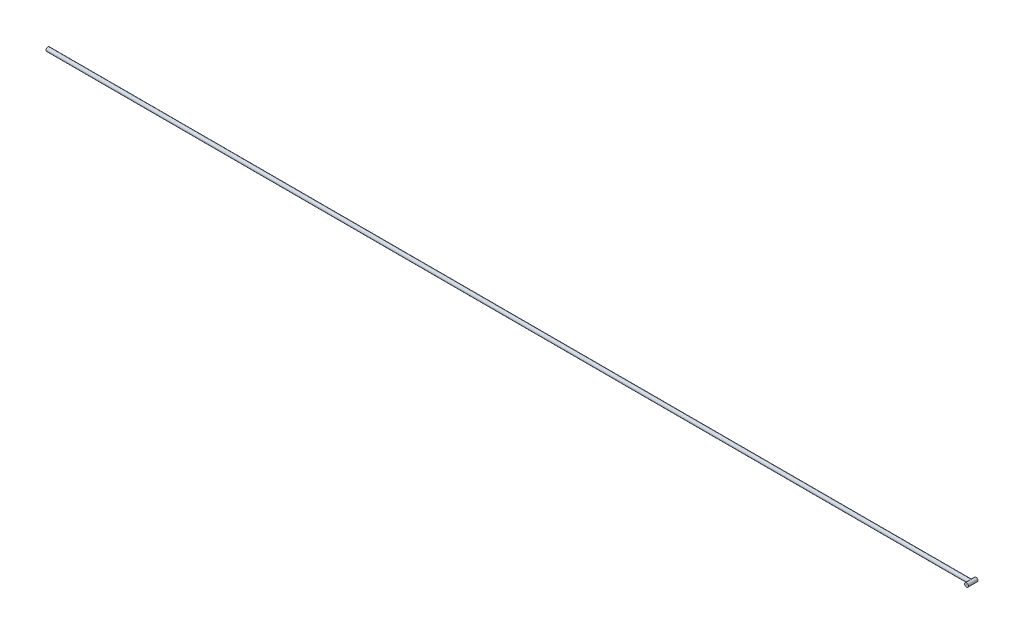
SolidWorks part; units mm, degrees
ref_plane "Plan de face" through (0, 0, 0) normal (0, 0, 1) x (1, 0, 0)
ref_plane "Plan de dessus" through (0, 0, 0) normal (0, 1, 0) x (1, 0, 0)
ref_plane "Plan de droite" through (0, 0, 0) normal (1, 0, 0) x (0, 0, -1)
sketch "Esquisse1" plane through (0, 0, 0) normal (0, 0, 1) x (1, 0, 0)
  line L0 (-240, 0) -> (240, 0)
  dimension "D1" = 480
sweep "Balayage1" add path "Esquisse1" circular profile diameter 2 parameters "D3"=2
sketch "Esquisse16" plane through (240, 0, 0) normal (1, 0, 0) x (0, 0, -1)
  line L0 (-2.5, 0) -> (2.5, 0)
  dimension "D1" = 5
sweep "Balayage2" add path "Esquisse16" circular profile diameter 2 parameters "D3"=2
